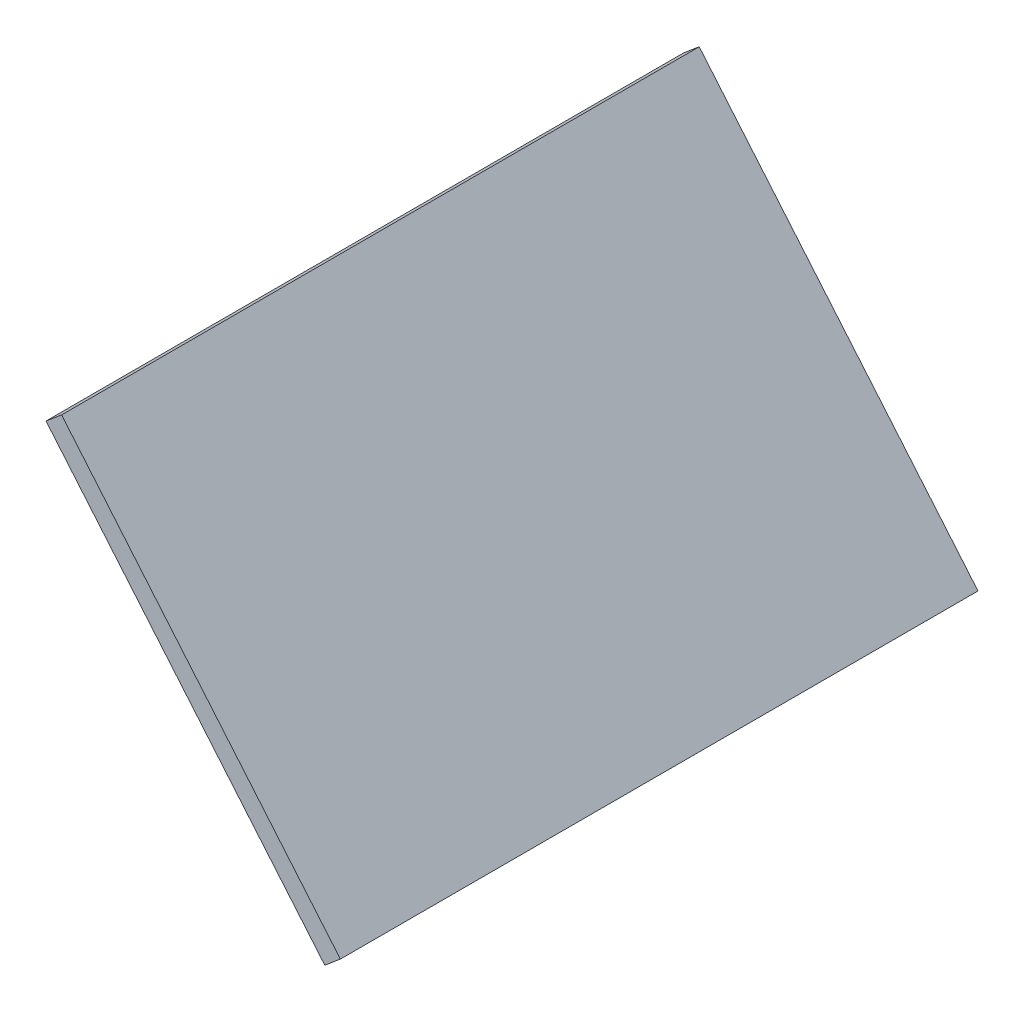
SolidWorks part; units mm, degrees
material "6061-T6 (SS)"
ref_plane "Front Plane" through (0, 0, 0) normal (0, 0, 1) x (1, 0, 0)
ref_plane "Top Plane" through (0, 0, 0) normal (0, 1, 0) x (1, 0, 0)
ref_plane "Right Plane" through (0, 0, 0) normal (1, 0, 0) x (0, 0, -1)
sketch "Sketch1" plane through (0, 0, 0) normal (0, 0, 1) x (1, 0, 0)
  line L0 (-45.6865, 0) -> (45.6865, 0) construction
  line L1 (0, -46.3862) -> (0, 46.3862) construction
  line L2 (-40.7891, 38.1) -> (40.7891, 38.1) construction
  line L3 (-16.002, -44.1473) -> (-16.002, 44.1473) construction
  line L4 (16.002, -46.666) -> (16.002, 46.666) construction
  line L5 (-16.002, 38.1) -> (16.002, 0)
  line L6 (16.002, 0) -> (12.827, 0)
  line L7 (-16.002, 38.1) -> (-19.177, 38.1)
  line L8 (-19.177, 38.1) -> (12.827, 0)
  point P4 (0, 0)
  point P8 (0, 0)
  point P11 (0, 38.1)
  point P14 (-16.002, 0)
  point P17 (16.002, 0)
  dimension "D1" = 38.1
  dimension "D2" = 16.002
  dimension "D3" = 16.002
  dimension "D4" = 3.175
  dimension "D5" = 3.175
extrude "Boss-Extrude1" add sketch "Sketch1" along normal mid plane 76.2
sketch "Sketch2" plane through (0, 0, 38.1) normal (0, 0, 1) x (1, 0, 0)
  line L0 (12.827, 0) -> (14.1405, -1.5637)
  line L1 (14.1405, -1.5637) -> (16.002, 0)
  line L2 (16.002, 0) -> (12.827, 0)
  line L3 (-16.002, 38.1) -> (-17.3155, 39.6637)
  line L4 (-17.3155, 39.6637) -> (-19.177, 38.1)
  line L5 (16.002, 0) -> (-16.002, 38.1) construction
  line L6 (-16.002, 38.1) -> (-19.177, 38.1)
extrude "Boss-Extrude2" add sketch "Sketch2" against normal up to surface (76.2 mm away) up to face at (-1.5875, 19.05, -38.1)
